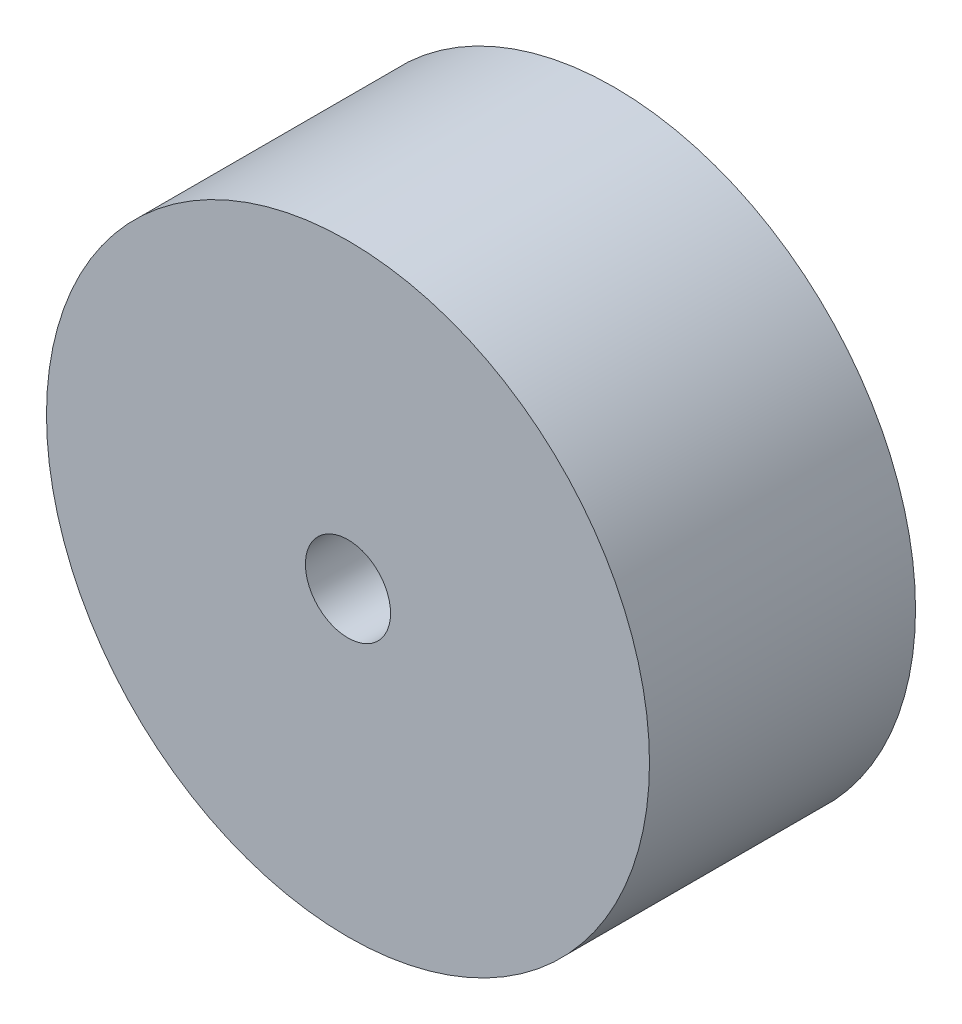
SolidWorks part; units mm, degrees
ref_plane "Front Plane" through (0, 0, 0) normal (0, 0, 1) x (1, 0, 0)
ref_plane "Top Plane" through (0, 0, 0) normal (0, 1, 0) x (1, 0, 0)
ref_plane "Right Plane" through (0, 0, 0) normal (1, 0, 0) x (0, 0, -1)
sketch "Sketch1" plane through (0, 0, 0) normal (0, 0, 1) x (1, 0, 0)
  circle A0 centre (0, 0) radius 21.59
  dimension "D1" = 43.18
extrude "Boss-Extrude1" add sketch "Sketch1" along normal blind 19.05
sketch "Sketch2" plane through (0, 0, 19.05) normal (0, 0, 1) x (1, 0, 0)
  circle A2 centre (0, 0) radius 3.048
  dimension "D1" = 6.096
extrude "Cut-Extrude2" cut sketch "Sketch2" against normal blind 7.62
sketch "Sketch3" plane through (0, 0, 0) normal (0, 0, -1) x (-1, 0, 0)
  circle A0 centre (0, 0) radius 6.35
  dimension "D1" = 12.7
extrude "Cut-Extrude3" cut sketch "Sketch3" against normal blind 7.62
